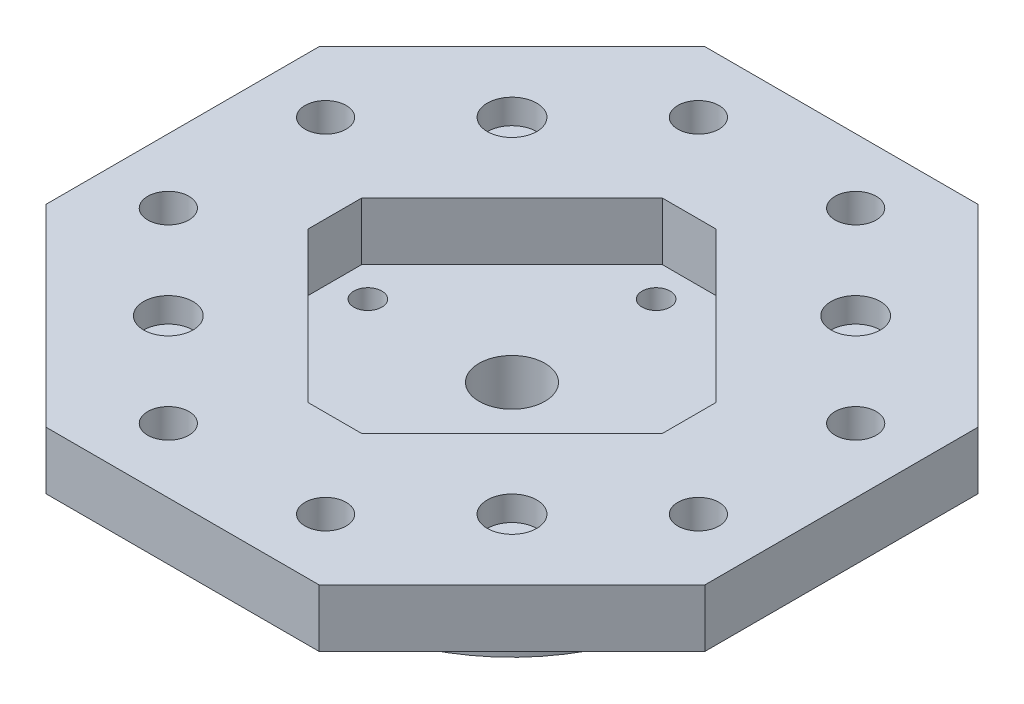
SolidWorks part; units mm, degrees
material "ABS"
ref_plane "Front" through (0, 0, 0) normal (0, 0, 1) x (1, 0, 0)
ref_plane "Top" through (0, 0, 0) normal (0, 1, 0) x (1, 0, 0)
ref_plane "Right" through (0, 0, 0) normal (1, 0, 0) x (0, 0, -1)
sketch "草图1" plane through (0, 0, 0) normal (0, 1, 0) x (1, 0, 0)
  circle A0 centre (0, 0) radius 27.5
  dimension "D1" = 55
extrude "凸台-拉伸1" add sketch "草图1" against normal blind 3
sketch "草图2" plane through (0, -3, 0) normal (0, -1, 0) x (1, 0, 0)
  circle A0 centre (0, 0) radius 22.5
  dimension "D1" = 45
extrude "凸台-拉伸2" add sketch "草图2" along normal blind 10
sketch "草图3" plane through (0, -13, 0) normal (0, -1, 0) x (1, 0, 0)
  circle A0 centre (0, 17.5) radius 1.7
  circle A1 centre (17.5, 0) radius 1.7
  circle A2 centre (0, -17.5) radius 1.7
  circle A3 centre (-17.5, 0) radius 1.7
  circle A4 centre (0, 0) radius 4
  point P12 (0, 0)
  dimension "D1" = 3.4
  dimension "D4" = 8
  dimension "D2" = 17.5
  dimension "D3" = 4
extrude "切除-拉伸1" cut sketch "草图3" against normal up to next
sketch "草图4" plane through (0, 0, 0) normal (0, 1, 0) x (1, 0, 0)
  line L0 (-66.0793, 0) -> (64.6468, 0) construction
  line L1 (0, 69.9547) -> (0, -71.394) construction
  line L2 (0, 21.5) -> (3.2487, 21.5)
  line L3 (3.2487, 21.5) -> (21.5, 3.2487)
  line L4 (21.5, 3.2487) -> (21.5, 0)
  line L5 (21.5, 0) -> (21.5, -3.2487)
  line L6 (21.5, -3.2487) -> (3.2487, -21.5)
  line L7 (3.2487, -21.5) -> (0, -21.5)
  line L8 (0, -21.5) -> (-3.2487, -21.5)
  line L9 (-3.2487, -21.5) -> (-21.5, -3.2487)
  line L10 (-21.5, -3.2487) -> (-21.5, 0)
  line L11 (-21.5, 0) -> (-21.5, 3.2487)
  line L12 (-21.5, 3.2487) -> (-3.2487, 21.5)
  line L13 (-3.2487, 21.5) -> (0, 21.5)
  line L18 (0, 40) -> (16.5685, 40)
  line L19 (16.5685, 40) -> (40, 16.5685)
  line L20 (40, 16.5685) -> (40, 0)
  line L21 (40, 0) -> (40, -16.5685)
  line L22 (16.5685, -40) -> (0, -40)
  line L23 (40, -16.5685) -> (16.5685, -40)
  line L24 (0, -40) -> (-16.5685, -40)
  line L25 (-40, -16.5685) -> (-40, 0)
  line L26 (-16.5685, -40) -> (-40, -16.5685)
  line L27 (-40, 0) -> (-40, 16.5685)
  line L28 (-16.5685, 40) -> (0, 40)
  line L29 (-40, 16.5685) -> (-16.5685, 40)
  circle A0 centre (0, 0) radius 27.5 construction
  point P24 (0, 0)
  point P29 (0, 0)
  point P40 (0, 0)
  dimension "D1" = 21.5
  dimension "D2" = 21.5
  dimension "D3" = 45
  dimension "D4" = 17.5
  dimension "D6" = 40
  dimension "D7" = 22.5
  dimension "D8" = 40
  dimension "D5" = 4
  dimension "D9" = 4
extrude "凸台-拉伸3" add sketch "草图4" along normal blind 7
sketch "草图6" plane through (0, 7, 0) normal (0, 1, 0) x (1, 0, 0)
  line L0 (0, 0) -> (42.1503, 42.1503) construction
  line L1 (21.5, 3.2487) -> (3.2487, 21.5) construction
  circle A0 centre (20.8597, 20.8597) radius 3
  circle A1 centre (20.8597, -20.8597) radius 3
  circle A2 centre (-20.8597, -20.8597) radius 3
  circle A3 centre (-20.8597, 20.8597) radius 3
  point P16 (0, 0)
  dimension "D1" = 6
  dimension "D2" = 12
extrude "切除-拉伸2" cut sketch "草图6" against normal blind 3
sketch "草图7" plane through (0, 7, 0) normal (0, 1, 0) x (1, 0, 0)
  line L0 (0, 0) -> (38.1237, 38.1237) construction
  line L1 (21.5, 3.2487) -> (3.2487, 21.5) construction
  line L3 (27.8626, 13.8567) -> (3.2196, 38.4997) construction
  circle A0 centre (9.5459, 32.1734) radius 2.5
  circle A1 centre (32.1734, 9.5459) radius 2.5
  circle A2 centre (32.1734, -9.5459) radius 2.5
  circle A3 centre (9.5459, -32.1734) radius 2.5
  circle A4 centre (-9.5459, -32.1734) radius 2.5
  circle A5 centre (-32.1734, -9.5459) radius 2.5
  circle A6 centre (-32.1734, 9.5459) radius 2.5
  circle A7 centre (-9.5459, 32.1734) radius 2.5
  point P24 (0, 0)
  dimension "D1" = 5
  dimension "D2" = 5
  dimension "D3" = 16
  dimension "D4" = 16
  dimension "D5" = 12
extrude "切除-拉伸3" cut sketch "草图7" against normal up to next
